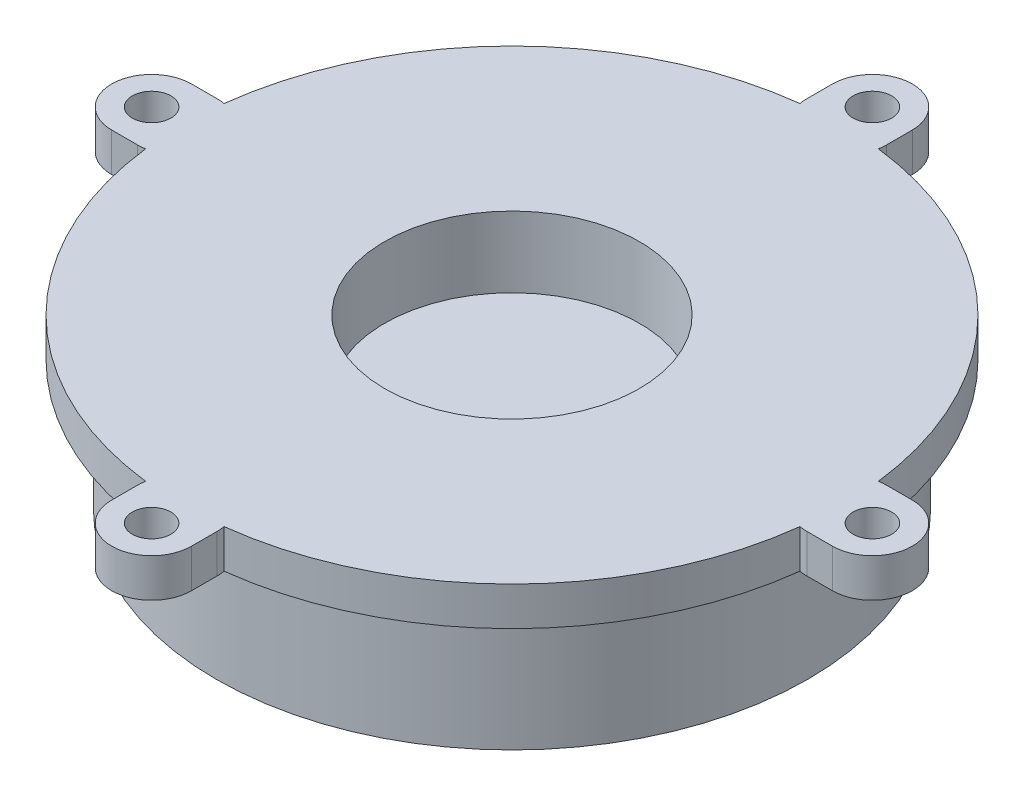
SolidWorks part; units mm, degrees
ref_plane "Front Plane" through (0, 0, 0) normal (0, 0, 1) x (1, 0, 0)
ref_plane "Top Plane" through (0, 0, 0) normal (0, 1, 0) x (1, 0, 0)
ref_plane "Right Plane" through (0, 0, 0) normal (1, 0, 0) x (0, 0, -1)
ref_plane "Plane1" through (0, 20, 0) normal (0, 1, 0) x (1, 0, 0)
sketch "Sketch1" plane through (0, 20, 0) normal (0, 1, 0) x (1, 0, 0)
  line L0 (-14.0762, 18.9987) -> (-14.0762, -37.0013) construction
  line L1 (13.9238, -9.0013) -> (-42.0762, -9.0013) construction
  line L2 (13.9238, -9.0013) -> (11.9238, -9.0013) construction
  line L3 (13.9238, -12.1013) -> (11.9238, -12.1013)
  line L4 (13.9238, -5.9013) -> (11.9238, -5.9013)
  line L5 (-14.0762, -37.0013) -> (-14.0762, -35.0013) construction
  line L6 (-17.1762, -37.0013) -> (-17.1762, -35.0013)
  line L7 (-10.9762, -37.0013) -> (-10.9762, -35.0013)
  line L8 (-40.0762, -9.0013) -> (-42.0762, -9.0013) construction
  line L9 (-40.0762, -12.1013) -> (-42.0762, -12.1013)
  line L10 (-40.0762, -5.9013) -> (-42.0762, -5.9013)
  line L11 (-14.0762, 16.9987) -> (-14.0762, 18.9987) construction
  line L12 (-17.1762, 16.9987) -> (-17.1762, 18.9987)
  line L13 (-10.9762, 16.9987) -> (-10.9762, 18.9987)
  circle A1 centre (-14.0762, -9.0013) radius 25.6
  arc A2 (13.9238, -12.1013) -> (13.9238, -5.9013) centre (13.9238, -9.0013) ccw
  arc A3 (11.9238, -5.9013) -> (11.9238, -12.1013) centre (11.9238, -9.0013) ccw
  arc A4 (-17.1762, -37.0013) -> (-10.9762, -37.0013) centre (-14.0762, -37.0013) ccw
  arc A5 (-10.9762, -35.0013) -> (-17.1762, -35.0013) centre (-14.0762, -35.0013) ccw
  arc A6 (-40.0762, -12.1013) -> (-40.0762, -5.9013) centre (-40.0762, -9.0013) ccw
  arc A7 (-42.0762, -5.9013) -> (-42.0762, -12.1013) centre (-42.0762, -9.0013) ccw
  arc A8 (-17.1762, 16.9987) -> (-10.9762, 16.9987) centre (-14.0762, 16.9987) ccw
  arc A9 (-10.9762, 18.9987) -> (-17.1762, 18.9987) centre (-14.0762, 18.9987) ccw
  circle A10 centre (13.9238, -9.0013) radius 1.5
  circle A11 centre (-14.0762, -37.0013) radius 1.5
  circle A12 centre (-42.0762, -9.0013) radius 1.5
  circle A13 centre (-14.0762, 18.9987) radius 1.5
  point P4 (12.9238, -9.0013)
  point P8 (-14.0762, -9.0013)
  point P12 (-14.0762, -9.0013)
  point P19 (-14.0762, -36.0013)
  point P26 (-41.0762, -9.0013)
  point P33 (-14.0762, 17.9987)
  dimension "D2" = 51.2
  dimension "D3" = 3.1
  dimension "D4" = 3
extrude "Boss-Extrude3" add sketch "Sketch1" along normal blind 1 contours L4 A3 A1 L3 A2 A10 | A1 A3 | A8 A1 A6 A5 A3 | L7 A5 A1 L6 A4 A11 | A1 A5 | A1 A6 | L13 A9 L12 A8 A1 A13 | A1 A8 | L10 A7 L9 A6 A1 A12
sketch "Sketch2" plane through (0, 20, 0) normal (0, -1, 0) x (1, 0, 0)
  line L0 (-14.0762, 40.1013) -> (-14.0762, -22.0987) construction
  arc A0 (-10.9762, 37.0013) -> (-17.1762, 37.0013) centre (-14.0762, 37.0013) ccw construction
  arc A1 (-17.1762, -18.9987) -> (-10.9762, -18.9987) centre (-14.0762, -18.9987) ccw construction
  circle A2 centre (-14.0762, 9.0013) radius 23
  dimension "D1" = 46
extrude "Boss-Extrude4" add sketch "Sketch2" along normal blind 3
sketch "Sketch7" plane through (0, 21, 0) normal (0, 1, 0) x (1, 0, 0)
  point P0 (-14.0762, -9.0013)
sketch "Sketch8" plane through (0, 17, 0) normal (0, -1, 0) x (1, 0, 0)
  circle A0 centre (-14.0762, 9.0013) radius 12.5
  circle A1 centre (-14.0762, 9.0013) radius 16.5
  dimension "D1" = 25
  dimension "D2" = 33
sketch "Sketch10" plane through (0, 21, 0) normal (0, 1, 0) x (1, 0, 0)
  line L16 (13.9238, -5.9013) -> (11.9238, -5.9013)
  line L17 (-10.9762, 16.9987) -> (-10.9762, 18.9987)
  line L18 (-17.1762, 18.9987) -> (-17.1762, 16.9987)
  line L19 (-40.0762, -5.9013) -> (-42.0762, -5.9013)
  line L20 (-42.0762, -12.1013) -> (-40.0762, -12.1013)
  line L21 (-17.1762, -35.0013) -> (-17.1762, -37.0013)
  line L22 (-10.9762, -37.0013) -> (-10.9762, -35.0013)
  line L23 (11.9238, -12.1013) -> (13.9238, -12.1013)
  line L24 (13.9238, -5.9013) -> (11.9238, -5.9013)
  line L25 (-10.9762, 16.9987) -> (-10.9762, 18.9987)
  line L26 (-17.1762, 18.9987) -> (-17.1762, 16.9987)
  line L27 (-40.0762, -5.9013) -> (-42.0762, -5.9013)
  line L28 (-42.0762, -12.1013) -> (-40.0762, -12.1013)
  line L29 (-17.1762, -35.0013) -> (-17.1762, -37.0013)
  line L30 (-10.9762, -37.0013) -> (-10.9762, -35.0013)
  line L31 (11.9238, -12.1013) -> (13.9238, -12.1013)
  arc A32 (11.9238, -5.9013) -> (11.342, -5.9564) centre (11.9238, -9.0013) ccw
  arc A33 (11.342, -5.9564) -> (-11.0313, 16.4169) centre (-14.0762, -9.0013) ccw
  arc A34 (-11.0313, 16.4169) -> (-10.9762, 16.9987) centre (-14.0762, 16.9987) ccw
  arc A35 (-10.9762, 18.9987) -> (-17.1762, 18.9987) centre (-14.0762, 18.9987) ccw
  arc A36 (-17.1762, 16.9987) -> (-17.1212, 16.4169) centre (-14.0762, 16.9987) ccw
  arc A37 (-17.1212, 16.4169) -> (-39.4945, -5.9564) centre (-14.0762, -9.0013) ccw
  arc A38 (-39.4945, -5.9564) -> (-40.0762, -5.9013) centre (-40.0762, -9.0013) ccw
  arc A39 (-42.0762, -5.9013) -> (-42.0762, -12.1013) centre (-42.0762, -9.0013) ccw
  arc A40 (-40.0762, -12.1013) -> (-39.4945, -12.0463) centre (-40.0762, -9.0013) ccw
  arc A41 (-39.4945, -12.0463) -> (-17.1212, -34.4196) centre (-14.0762, -9.0013) ccw
  arc A42 (-17.1212, -34.4196) -> (-17.1762, -35.0013) centre (-14.0762, -35.0013) ccw
  arc A43 (-17.1762, -37.0013) -> (-10.9762, -37.0013) centre (-14.0762, -37.0013) ccw
  arc A44 (-10.9762, -35.0013) -> (-11.0313, -34.4196) centre (-14.0762, -35.0013) ccw
  arc A45 (-11.0313, -34.4196) -> (11.342, -12.0463) centre (-14.0762, -9.0013) ccw
  arc A46 (11.342, -12.0463) -> (11.9238, -12.1013) centre (11.9238, -9.0013) ccw
  arc A47 (13.9238, -12.1013) -> (13.9238, -5.9013) centre (13.9238, -9.0013) ccw
  arc A48 (11.9238, -5.9013) -> (11.342, -5.9564) centre (11.9238, -9.0013) ccw
  arc A49 (11.342, -5.9564) -> (-11.0313, 16.4169) centre (-14.0762, -9.0013) ccw
  arc A50 (-11.0313, 16.4169) -> (-10.9762, 16.9987) centre (-14.0762, 16.9987) ccw
  arc A51 (-10.9762, 18.9987) -> (-17.1762, 18.9987) centre (-14.0762, 18.9987) ccw
  arc A52 (-17.1762, 16.9987) -> (-17.1212, 16.4169) centre (-14.0762, 16.9987) ccw
  arc A53 (-17.1212, 16.4169) -> (-39.4945, -5.9564) centre (-14.0762, -9.0013) ccw
  arc A54 (-39.4945, -5.9564) -> (-40.0762, -5.9013) centre (-40.0762, -9.0013) ccw
  arc A55 (-42.0762, -5.9013) -> (-42.0762, -12.1013) centre (-42.0762, -9.0013) ccw
  arc A56 (-40.0762, -12.1013) -> (-39.4945, -12.0463) centre (-40.0762, -9.0013) ccw
  arc A57 (-39.4945, -12.0463) -> (-17.1212, -34.4196) centre (-14.0762, -9.0013) ccw
  arc A58 (-17.1212, -34.4196) -> (-17.1762, -35.0013) centre (-14.0762, -35.0013) ccw
  arc A59 (-17.1762, -37.0013) -> (-10.9762, -37.0013) centre (-14.0762, -37.0013) ccw
  arc A60 (-10.9762, -35.0013) -> (-11.0313, -34.4196) centre (-14.0762, -35.0013) ccw
  arc A61 (-11.0313, -34.4196) -> (11.342, -12.0463) centre (-14.0762, -9.0013) ccw
  arc A62 (11.342, -12.0463) -> (11.9238, -12.1013) centre (11.9238, -9.0013) ccw
  arc A63 (13.9238, -12.1013) -> (13.9238, -5.9013) centre (13.9238, -9.0013) ccw
  dimension "D1" = 0
extrude "Boss-Extrude5" add sketch "Sketch10" along normal blind 2
sketch "Sketch11" plane through (0, 21, 0) normal (0, -1, 0) x (1, 0, 0)
  circle A2 centre (-14.0762, 37.0013) radius 1.5
  circle A3 centre (-14.0762, 37.0013) radius 1.5
  dimension "D1" = 0
extrude "Cut-Extrude1" cut sketch "Sketch11" against normal through all
sketch "Sketch12" plane through (0, 21, 0) normal (0, -1, 0) x (1, 0, 0)
  circle A2 centre (13.9238, 9.0013) radius 1.5
  circle A3 centre (13.9238, 9.0013) radius 1.5
  dimension "D1" = 0
extrude "Cut-Extrude2" cut sketch "Sketch12" against normal blind 6
sketch "Sketch13" plane through (0, 21, 0) normal (0, -1, 0) x (1, 0, 0)
  circle A2 centre (-42.0762, 9.0013) radius 1.5
  circle A3 centre (-42.0762, 9.0013) radius 1.5
  dimension "D1" = 0
extrude "Cut-Extrude3" cut sketch "Sketch13" against normal through all
sketch "Sketch14" plane through (0, 21, 0) normal (0, -1, 0) x (1, 0, 0)
  circle A2 centre (-14.0762, -18.9987) radius 1.5
  circle A3 centre (-14.0762, -18.9987) radius 1.5
  dimension "D1" = 0
extrude "Cut-Extrude4" cut sketch "Sketch14" against normal through all
sketch "Sketch15" plane through (0, 17, 0) normal (0, -1, 0) x (1, 0, 0)
extrude "Cut-Extrude5" cut sketch "Sketch8" against normal blind 4
sketch "Sketch16" plane through (0, 23, 0) normal (0, 1, 0) x (1, 0, 0)
  line L0 (-14.0762, -9.0013) -> (-15.7239, -9.0013) construction
  line L1 (-19.0239, -6.2013) -> (-19.0239, -7.3013)
  line L2 (-19.0239, -11.2013) -> (-23.4239, -11.2013)
  line L3 (-23.4239, -11.2013) -> (-23.4239, -6.2013)
  line L4 (-23.4239, -6.2013) -> (-19.0239, -6.2013)
  line L5 (-19.0239, -10.7013) -> (-19.0239, -11.2013)
  line L6 (-15.7239, -7.3013) -> (-19.0239, -7.3013)
  line L7 (-15.7239, -7.3013) -> (-15.7239, -10.7013)
  line L8 (-15.7239, -10.7013) -> (-19.0239, -10.7013)
  line L10 (-14.0762, -9.0013) -> (-16.711, -4.4378) construction
  line L11 (-14.0762, -9.0013) -> (-15.9993, -12.3321) construction
  line L12 (-14.7247, -11.2782) -> (-13.0747, -14.1361)
  line L13 (-13.0747, -14.1361) -> (-13.5077, -14.3861)
  line L14 (-13.5077, -14.3861) -> (-11.3077, -18.1966)
  line L15 (-11.3077, -18.1966) -> (-6.9775, -15.6966)
  line L16 (-6.9775, -15.6966) -> (-9.1775, -11.8861)
  line L17 (-9.1775, -11.8861) -> (-10.1302, -12.4361)
  line L18 (-11.7802, -9.5782) -> (-10.1302, -12.4361)
  line L19 (-11.7802, -9.5782) -> (-14.7247, -11.2782)
  line L20 (-11.7802, -8.4244) -> (-10.1302, -5.5665)
  line L21 (-10.1302, -5.5665) -> (-9.6972, -5.8165)
  line L22 (-9.6972, -5.8165) -> (-7.4972, -2.006)
  line L23 (-7.4972, -2.006) -> (-11.8273, 0.494)
  line L24 (-14.0273, -3.3165) -> (-13.0747, -3.8665)
  line L25 (-11.8273, 0.494) -> (-14.0273, -3.3165)
  line L26 (-14.7247, -6.7244) -> (-13.0747, -3.8665)
  line L27 (-14.7247, -6.7244) -> (-11.7802, -8.4244)
  circle A0 centre (-14.0762, -9.0013) radius 9.9
  point P7 (-19.0239, -9.0013)
  point P8 (-19.0239, -9.0013)
  dimension "D1" = 19.8
  dimension "D2" = 60
  dimension "D3" = 5
  dimension "D4" = 4.4
  dimension "D5" = 3.4
  dimension "D6" = 60
extrude "Cut-Extrude7" cut sketch "Sketch16" against normal blind 2
sketch "Sketch17" plane through (0, 23, 0) normal (0, 1, 0) x (1, 0, 0)
  line L16 (-19.0239, -6.2013) -> (-23.4239, -6.2013)
  line L17 (-23.4239, -6.2013) -> (-23.4239, -11.2013)
  line L18 (-23.4239, -11.2013) -> (-19.0239, -11.2013)
  line L19 (-19.0239, -11.2013) -> (-19.0239, -10.7013)
  line L20 (-19.0239, -10.7013) -> (-15.7239, -10.7013)
  line L21 (-15.7239, -10.7013) -> (-15.7239, -7.3013)
  line L22 (-15.7239, -7.3013) -> (-19.0239, -7.3013)
  line L23 (-19.0239, -7.3013) -> (-19.0239, -6.2013)
  line L24 (-19.0239, -6.2013) -> (-23.4239, -6.2013)
  line L25 (-23.4239, -6.2013) -> (-23.4239, -11.2013)
  line L26 (-23.4239, -11.2013) -> (-19.0239, -11.2013)
  line L27 (-19.0239, -11.2013) -> (-19.0239, -10.7013)
  line L28 (-19.0239, -10.7013) -> (-15.7239, -10.7013)
  line L29 (-15.7239, -10.7013) -> (-15.7239, -7.3013)
  line L30 (-15.7239, -7.3013) -> (-19.0239, -7.3013)
  line L31 (-19.0239, -7.3013) -> (-19.0239, -6.2013)
  dimension "D1" = 0
extrude "Cut-Extrude8" cut sketch "Sketch17" against normal blind 5.5
sketch "Sketch18" plane through (0, 23, 0) normal (0, 1, 0) x (1, 0, 0)
  line L16 (-10.1302, -12.4361) -> (-11.7802, -9.5782)
  line L17 (-11.7802, -9.5782) -> (-14.7247, -11.2782)
  line L18 (-14.7247, -11.2782) -> (-13.0747, -14.1361)
  line L19 (-13.0747, -14.1361) -> (-13.5077, -14.3861)
  line L20 (-13.5077, -14.3861) -> (-11.3077, -18.1966)
  line L21 (-11.3077, -18.1966) -> (-6.9775, -15.6966)
  line L22 (-6.9775, -15.6966) -> (-9.1775, -11.8861)
  line L23 (-9.1775, -11.8861) -> (-10.1302, -12.4361)
  line L24 (-10.1302, -12.4361) -> (-11.7802, -9.5782)
  line L25 (-11.7802, -9.5782) -> (-14.7247, -11.2782)
  line L26 (-14.7247, -11.2782) -> (-13.0747, -14.1361)
  line L27 (-13.0747, -14.1361) -> (-13.5077, -14.3861)
  line L28 (-13.5077, -14.3861) -> (-11.3077, -18.1966)
  line L29 (-11.3077, -18.1966) -> (-6.9775, -15.6966)
  line L30 (-6.9775, -15.6966) -> (-9.1775, -11.8861)
  line L31 (-9.1775, -11.8861) -> (-10.1302, -12.4361)
  dimension "D1" = 0
extrude "Cut-Extrude9" cut sketch "Sketch18" against normal blind 5.5
sketch "Sketch19" plane through (0, 23, 0) normal (0, 1, 0) x (1, 0, 0)
  line L16 (-13.0747, -3.8665) -> (-14.7247, -6.7244)
  line L17 (-14.7247, -6.7244) -> (-11.7802, -8.4244)
  line L18 (-11.7802, -8.4244) -> (-10.1302, -5.5665)
  line L19 (-10.1302, -5.5665) -> (-9.6972, -5.8165)
  line L20 (-9.6972, -5.8165) -> (-7.4972, -2.006)
  line L21 (-7.4972, -2.006) -> (-11.8273, 0.494)
  line L22 (-11.8273, 0.494) -> (-14.0273, -3.3165)
  line L23 (-14.0273, -3.3165) -> (-13.0747, -3.8665)
  line L24 (-13.0747, -3.8665) -> (-14.7247, -6.7244)
  line L25 (-14.7247, -6.7244) -> (-11.7802, -8.4244)
  line L26 (-11.7802, -8.4244) -> (-10.1302, -5.5665)
  line L27 (-10.1302, -5.5665) -> (-9.6972, -5.8165)
  line L28 (-9.6972, -5.8165) -> (-7.4972, -2.006)
  line L29 (-7.4972, -2.006) -> (-11.8273, 0.494)
  line L30 (-11.8273, 0.494) -> (-14.0273, -3.3165)
  line L31 (-14.0273, -3.3165) -> (-13.0747, -3.8665)
  dimension "D1" = 0
extrude "Cut-Extrude10" cut sketch "Sketch19" against normal blind 5.5
sketch "Sketch20" plane through (0, 21, 0) normal (0, 1, 0) x (1, 0, 0)
  circle A2 centre (-14.0762, -9.0013) radius 9.9
  circle A3 centre (-14.0762, -9.0013) radius 9.9
  dimension "D1" = 0
extrude "Cut-Extrude11" cut sketch "Sketch20" against normal blind 1
sketch "Sketch21" plane through (0, 17, 0) normal (0, -1, 0) x (1, 0, 0)
  circle A0 centre (-14.0762, 9.0013) radius 0.5
  dimension "D1" = 1
extrude "Cut-Extrude12" cut sketch "Sketch21" against normal blind 2
sketch "Sketch24" plane through (0, 17, 0) normal (0, -1, 0) x (1, 0, 0)
  circle A0 centre (-14.0762, 9.0013) radius 16.5 construction
  circle A1 centre (-14.0762, 9.0013) radius 23
  circle A2 centre (-14.0762, 9.0013) radius 23
  circle A3 centre (-14.0762, 9.0013) radius 16.5
  dimension "D1" = 0
extrude "Boss-Extrude6" add sketch "Sketch24" along normal blind 7
sketch "Sketch26" plane through (0, 20, 0) normal (0, 1, 0) x (1, 0, 0)
  circle A3 centre (-14.0762, -9.0013) radius 9.9
  circle A4 centre (-14.0762, -9.0013) radius 9.9
  dimension "D1" = 0
extrude "Cut-Extrude13" cut sketch "Sketch26" against normal up to surface (2.5 mm away)
sketch "Sketch27" plane through (0, 17, 0) normal (0, -1, 0) x (1, 0, 0)
  circle A0 centre (-14.0762, 9.0013) radius 0.5
extrude "Boss-Extrude8" add sketch "Sketch27" against normal up to surface (0.5 mm away)
equation "\"LidDia\"=46"
equation "\"LidCentre\"=51.2"
equation "\"D2@Sketch1\"=\"LidCentre\""
equation "\"Hole\"=3"
equation "\"D4@Sketch1\"=\"Hole\""
equation "\"Extraextrude\"=3.1"
equation "\"D3@Sketch1\"=\"Extraextrude\""
equation "\"LidExtrude\"=46"
equation "\"D1@Sketch2\"=\"LidExtrude\""
equation "\"bridge_outer_diameter\"= 32"
equation "\"bridge_inner_diameter\"= 26"
equation "\"D1@Sketch8\"=\"bridge_inner_diameter\"-1"
equation "\"D2@Sketch8\"=\"bridge_outer_diameter\"+1"
